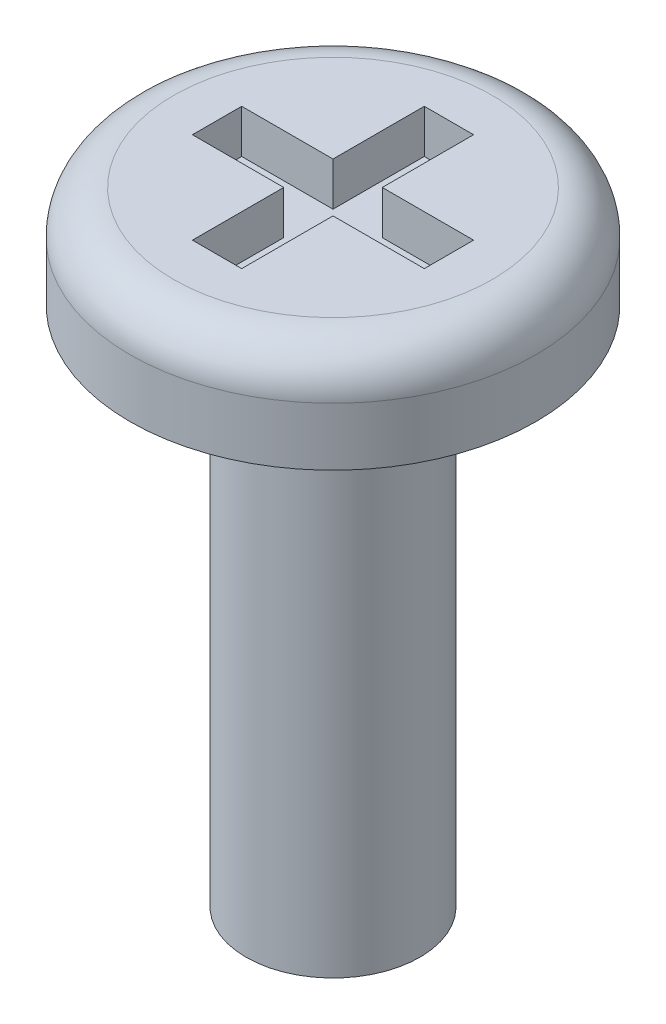
SolidWorks part; units mm, degrees
ref_plane "Front Plane" through (0, 0, 0) normal (0, 0, 1) x (1, 0, 0)
ref_plane "Top Plane" through (0, 0, 0) normal (0, 1, 0) x (1, 0, 0)
ref_plane "Right Plane" through (0, 0, 0) normal (1, 0, 0) x (0, 0, -1)
sketch "Sketch3" plane through (0, 0, 0) normal (0, 1, 0) x (1, 0, 0)
  circle A0 centre (0, 0) radius 1.5
  dimension "D1" = 3
extrude "Boss-Extrude1" add sketch "Sketch3" along normal blind 9
sketch "Sketch4" plane through (0, 9, 0) normal (0, 1, 0) x (1, 0, 0)
  circle A0 centre (0, 0) radius 3.5
  dimension "D1" = 7
extrude "Boss-Extrude2" add sketch "Sketch4" along normal blind 1.75
fillet "Fillet3" radius 0.75 1 edges at (0, 10.75, 3.5)
sketch "Sketch6" plane through (0, 10.75, 0) normal (0, 1, 0) x (1, 0, 0)
  line L0 (0.425, 0.425) -> (2, 0.425)
  line L1 (-2, 0.425) -> (-0.425, 0.425)
  line L2 (-2, 0.425) -> (-2, -0.425)
  line L3 (-2, -0.425) -> (-0.425, -0.425)
  line L4 (2, 0.425) -> (2, -0.425)
  line L5 (0, 0) -> (0.425, -0.0903) construction
  line L7 (-0.425, 2) -> (0.425, 2)
  line L8 (-0.425, 2) -> (-0.425, 0.425)
  line L9 (-0.425, -2) -> (0.425, -2)
  line L10 (0.425, 2) -> (0.425, 0.425)
  line L14 (-0.425, -0.425) -> (-0.425, -2)
  line L17 (0.425, -0.425) -> (0.425, -2)
  line L19 (0.425, -0.425) -> (2, -0.425)
  point P0 (0, 0)
  point P6 (0, 0)
  dimension "D1" = 4
  dimension "D2" = 4
  dimension "D3" = 0.85
  dimension "D4" = 0.85
extrude "Cut-Extrude4" cut sketch "Sketch6" against normal blind 0.75
sketch "Sketch7" plane through (0, 0, 0) normal (0, 0, 1) x (1, 0, 0)
  line L0 (-7.4335, 8) -> (10.8456, 8)
  dimension "D1" = 8
split line "Split Line1"
fillet "Fillet4" radius 0.25 1 edges at (0, 9, 1.5)
